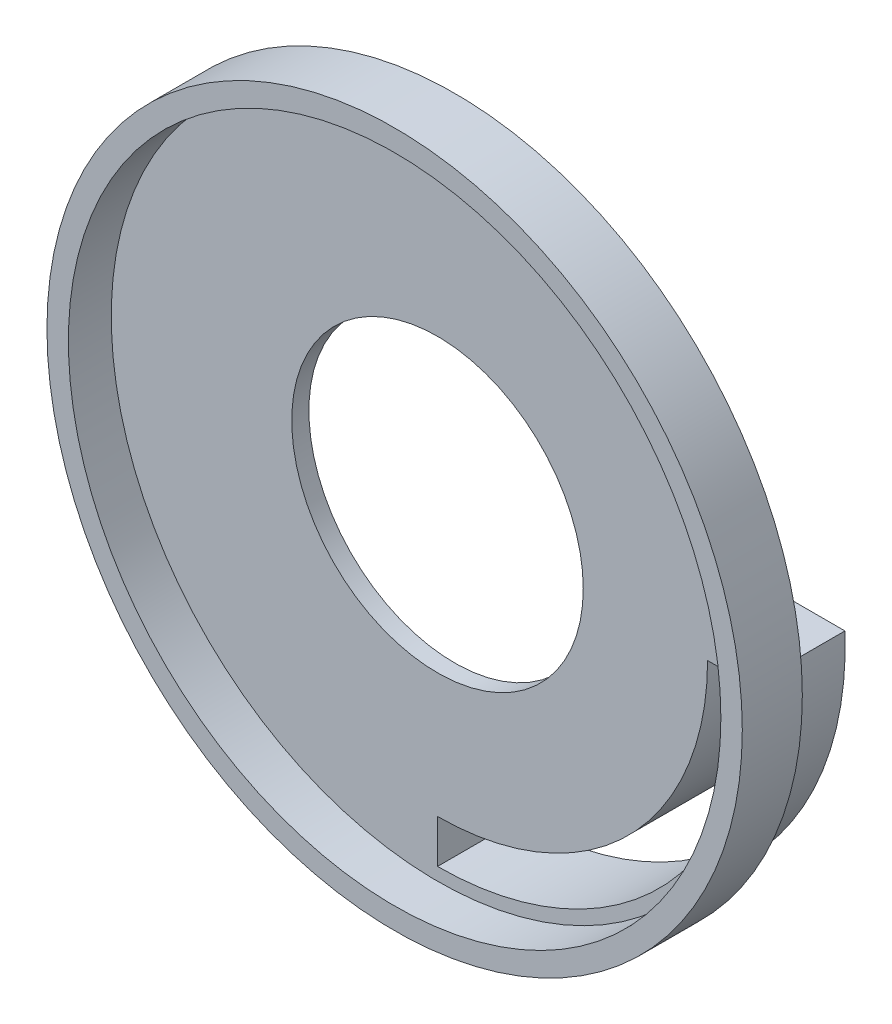
SolidWorks part; units mm, degrees
ref_plane "정면" through (0, 0, 0) normal (0, 0, 1) x (1, 0, 0)
ref_plane "윗면" through (0, 0, 0) normal (0, 1, 0) x (1, 0, 0)
ref_plane "우측면" through (0, 0, 0) normal (1, 0, 0) x (0, 0, -1)
sketch "스케치1" plane through (0, 0, 0) normal (0, 0, 1) x (1, 0, 0)
  circle A0 centre (0, 0) radius 76.1
  circle A1 centre (0, 0) radius 34
  dimension "D1" = 68
  dimension "D2" = 152.2
extrude "보스-돌출1" add sketch "스케치1" along normal blind 4
sketch "스케치2" plane through (0, 0, 4) normal (0, 0, 1) x (1, 0, 0)
  circle A0 centre (0, 0) radius 34 construction
  circle A1 centre (0, 0) radius 76.1
  circle A2 centre (0, 0) radius 76.1
  circle A3 centre (0, 0) radius 34
  circle A4 centre (0, 0) radius 81.1
  circle M2 centre (0, 0) radius 76.1
  dimension "D2" = 5
  dimension "D1" = 0
extrude "보스-돌출2" add sketch "스케치2" along normal blind 10 and the other way blind 4 contours A4 M2
sketch "스케치3" plane through (0, 0, 4) normal (0, 0, 1) x (1, 0, 0)
  line L0 (63, 0) -> (73.1, 0)
  line L1 (0, -63) -> (0, -73.1)
  arc A0 (63, 0) -> (0, -63) centre (0, 0) cw
  arc A2 (73.1, 0) -> (0, -73.1) centre (0, 0) cw
  circle M1 centre (0, 0) radius 76.1
  dimension "D1" = 63
  dimension "D2" = 73.1
extrude "컷-돌출1" cut sketch "스케치3" against normal blind 5 contours L0 A0 L1 M1
sketch "스케치4" plane through (0, 0, 0) normal (0, 0, -1) x (-1, 0, 0)
  line L0 (-63, 0) -> (-73.1, 0) construction
  line L1 (0, -63) -> (0, -73.1) construction
  line L2 (-63, 0) -> (-73.1, 0)
  line L3 (0, -63) -> (0, -73.1)
  line L4 (-59.925, 3) -> (-76.0408, 3)
  line L5 (3, -59.925) -> (3, -76.0408)
  arc A0 (-73.1, 0) -> (0, -73.1) centre (0, 0) ccw construction
  arc A1 (-63, 0) -> (0, -63) centre (0, 0) ccw construction
  arc A2 (-73.1, 0) -> (0, -73.1) centre (0, 0) ccw
  arc A3 (-63, 0) -> (0, -63) centre (0, 0) ccw
  arc A4 (-76.0408, 3) -> (3, -76.0408) centre (0, 0) ccw
  arc A5 (-59.925, 3) -> (3, -59.925) centre (0, 0) ccw
  dimension "D1" = 3
extrude "보스-돌출3" add sketch "스케치4" along normal blind 15
sketch "스케치5" plane through (0, 0, 0) normal (0, 0, -1) x (-1, 0, 0)
  line L2 (-59.925, 3) -> (-76.0408, 3)
  line L3 (3, -76.0408) -> (3, -59.925)
  line L4 (-59.925, 3) -> (-76.0408, 3)
  line L5 (3, -76.0408) -> (3, -59.925)
  arc A2 (-59.925, 3) -> (3, -59.925) centre (0, 0) ccw
  arc A3 (-76.0408, 3) -> (3, -76.0408) centre (0, 0) ccw
  arc A4 (-59.925, 3) -> (3, -59.925) centre (0, 0) ccw
  arc A5 (-76.0408, 3) -> (3, -76.0408) centre (0, 0) ccw
  dimension "D1" = 0
